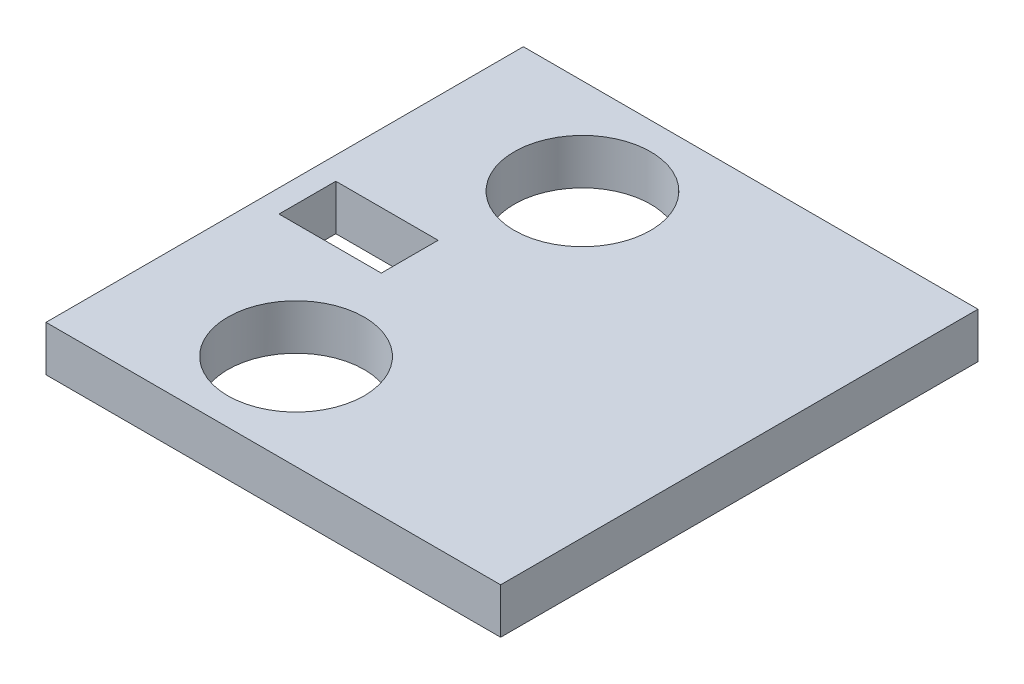
SolidWorks part; units mm, degrees
ref_plane "Front Plane" through (0, 0, 0) normal (0, 0, 1) x (1, 0, 0)
ref_plane "Top Plane" through (0, 0, 0) normal (0, 1, 0) x (1, 0, 0)
ref_plane "Right Plane" through (0, 0, 0) normal (1, 0, 0) x (0, 0, -1)
sketch "Sketch2" plane through (0, 0, 0) normal (0, 1, 0) x (1, 0, 0)
  line L0 (0, 80.9892) -> (0, -86.3988) construction
  line L1 (-50, 52.5) -> (50, 52.5)
  line L2 (-50, 52.5) -> (-50, -52.5)
  line L3 (-50, -52.5) -> (50, -52.5)
  line L4 (50, 52.5) -> (50, -52.5)
  line L5 (-89.0263, 0) -> (108.6553, 0) construction
  dimension "D1" = 100
  dimension "D2" = 105
extrude "Boss-Extrude1" add sketch "Sketch2" along normal blind 10
sketch "Sketch5" plane through (0, 0, 0) normal (0, -1, 0) x (1, 0, 0)
  line L0 (120.2435, 0) -> (-132.425, 0) construction
  line L1 (0, 87.6866) -> (0, -77.6809) construction
  line L4 (-50, 52.5) -> (50, 52.5) construction
  line L6 (-50, -52.5) -> (-50, 52.5) construction
  circle A0 centre (-39, 0) radius 39 construction
  circle A1 centre (-16.0054, 31.5) radius 15
  circle A2 centre (0, 0) radius 15 construction
  circle A4 centre (-39, 0) radius 5
  dimension "D1" = 30
  dimension "D2" = 6
  dimension "D3" = 30
  dimension "D4" = 10
  dimension "D6" = 78
  dimension "D5" = 6
extrude "Cut-Extrude1" cut sketch "Sketch5" against normal up to next
mirror "Mirror1" about plane through (0, 0, 0) normal (0, 0, 1) of "Cut-Extrude1"
sketch "Sketch6" plane through (0, 0, 0) normal (0, -1, 0) x (1, 0, 0)
  line L0 (-56.8508, 0) -> (61.7627, 0) construction
  line L1 (-45, 6.25) -> (-22.5, 6.25)
  line L2 (-45, 6.25) -> (-45, -6.25)
  line L3 (-45, -6.25) -> (-22.5, -6.25)
  line L4 (-22.5, 6.25) -> (-22.5, -6.25)
  circle A0 centre (-39, 0) radius 5 construction
  circle A1 centre (-39, 0) radius 5 construction
  dimension "D1" = 22.5
  dimension "D2" = 12.5
  dimension "D3" = 6
extrude "Cut-Extrude2" cut sketch "Sketch6" against normal up to next
